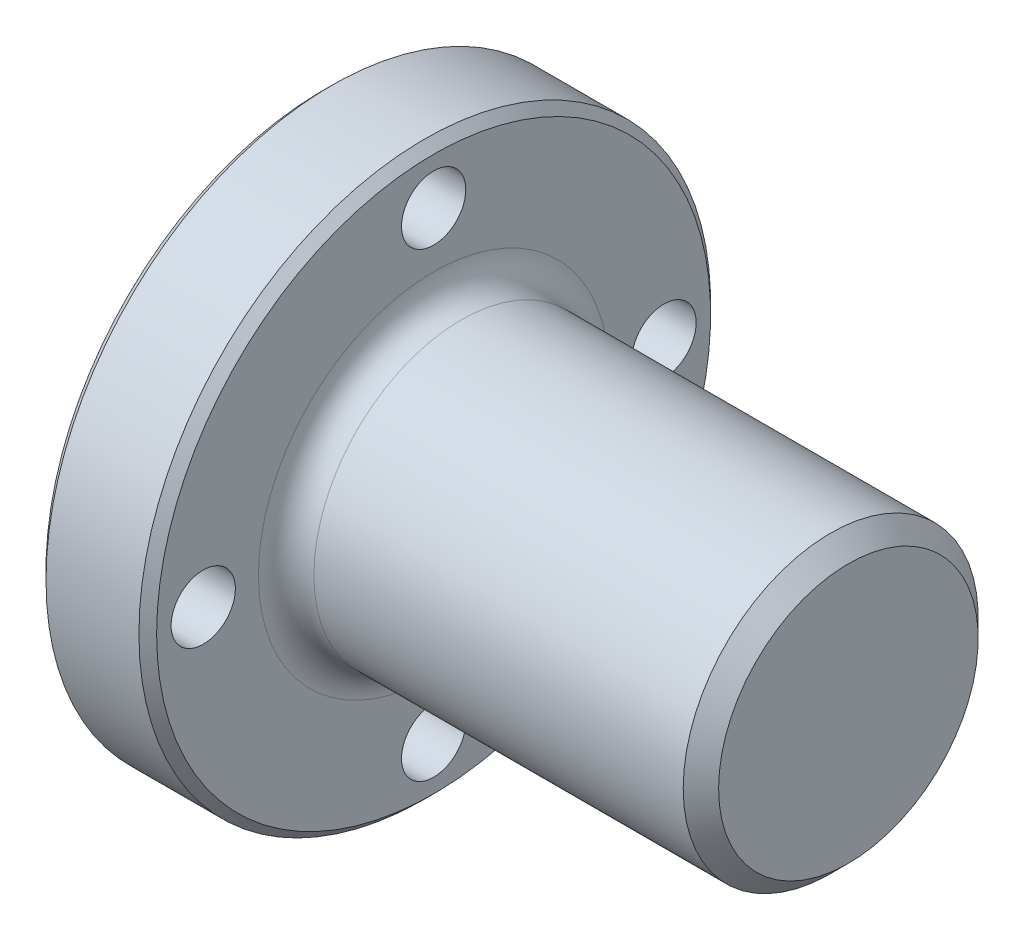
SolidWorks part; units mm, degrees
ref_plane "Front Plane" through (0, 0, 0) normal (1, 0, 0) x (0, 1, 0)
ref_plane "Top Plane" through (0, 0, 0) normal (0, 0, 1) x (0, 1, 0)
ref_plane "Right Plane" through (0, 0, 0) normal (0, 1, 0) x (-1, 0, 0)
sketch "Sketch1" plane through (0, 0, 0) normal (0, 0, 1) x (0, 1, 0)
  line L0 (0, 0) -> (8.7122, 0)
  line L1 (8.7122, 0) -> (8.7122, -4.826)
  line L2 (8.7122, -4.826) -> (24.6126, -4.826)
  line L3 (24.6126, -4.826) -> (24.6126, -14.351)
  line L4 (24.6126, -14.351) -> (12.7, -14.351)
  line L5 (12.7, -14.351) -> (12.7, -50.0634)
  line L6 (12.7, -50.0634) -> (0, -50.0634)
  line L7 (0, -50.0634) -> (0, 0)
  line L8 (0, 25.4) -> (0, -75.4634) construction
revolve "Revolve1" add sketch "Sketch1" angle 360 about L8
fillet "Fillet1" radius 2.3876 1 edges at (14.351, 0, 12.7)
chamfer "Chamfer1" distance 0.762 angle 45 3 edges at (14.351, 0, 24.6126) (4.826, 0, 24.6126) (0, 0, 8.7122)
chamfer "Chamfer2" distance 1.524 angle 45 1 edges at (50.0634, 0, 12.7)
sketch "Sketch2" plane through (0, 0, 0) normal (1, 0, 0) x (0, 1, 0)
  circle A0 centre (19.8374, 0) radius 2.7686
extrude "Cut-Extrude2" cut sketch "Sketch2" against normal through all from offset 14.351
sketch "Sketch3" plane through (0, 0, 0) normal (1, 0, 0) x (0, 1, 0)
  circle A0 centre (0, 19.8374) radius 2.7686
  circle A1 centre (-19.8374, 0) radius 2.7686
  circle A2 centre (0, -19.8374) radius 2.7686
extrude "Cut-Extrude4" cut sketch "Sketch3" against normal through all from offset 14.351
